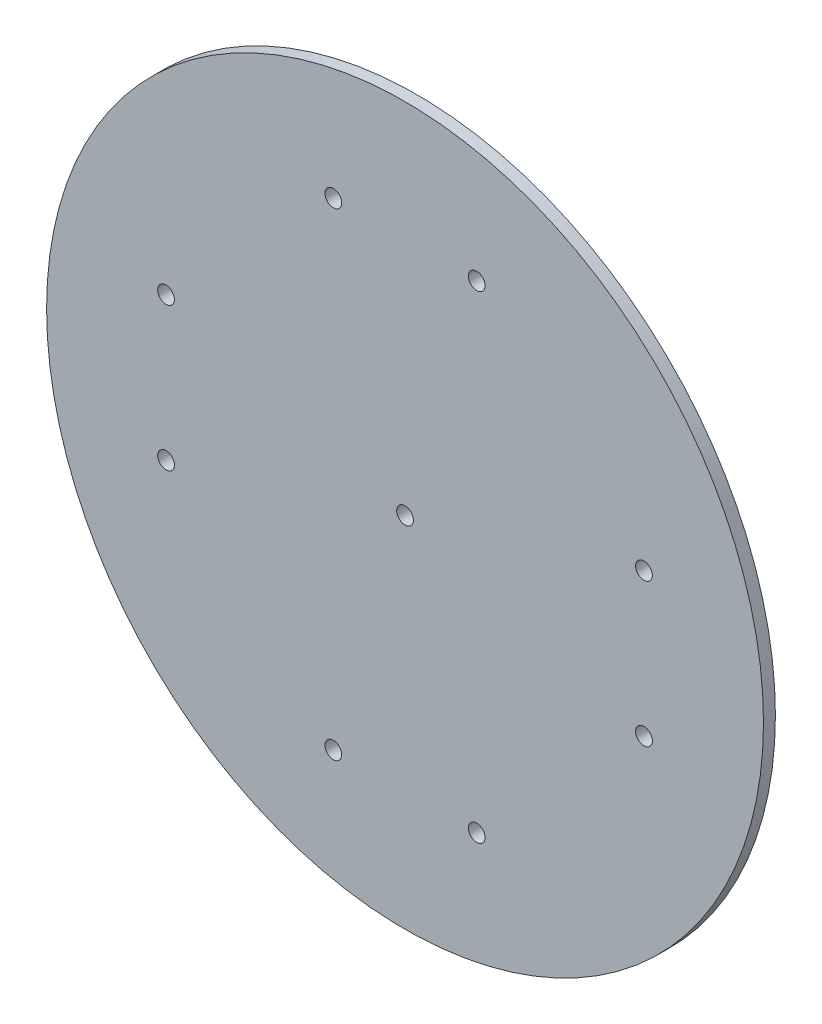
SolidWorks part; units mm, degrees
ref_plane "Front Plane" through (0, 0, 0) normal (0, 0, 1) x (1, 0, 0)
ref_plane "Top Plane" through (0, 0, 0) normal (0, 1, 0) x (1, 0, 0)
ref_plane "Right Plane" through (0, 0, 0) normal (1, 0, 0) x (0, 0, -1)
sketch "Sketch1" plane through (0, 0, 0) normal (0, 0, 1) x (1, 0, 0)
  circle A0 centre (0, 0) radius 75
  dimension "D1" = 150
extrude "Boss-Extrude1" add sketch "Sketch1" along normal blind 2.5
sketch "Sketch2" plane through (0, 0, 0) normal (0, 0, -1) x (-1, 0, 0)
  line L1 (-50, 15) -> (50, 15) construction
  line L2 (-50, 15) -> (-50, -15) construction
  line L3 (-50, -15) -> (50, -15) construction
  line L4 (50, 15) -> (50, -15) construction
  line L5 (-50, 15) -> (50, -15) construction
  line L6 (-50, -15) -> (50, 15) construction
  line L7 (-15, 50) -> (15, 50) construction
  line L8 (-15, 50) -> (-15, -50) construction
  line L9 (-15, -50) -> (15, -50) construction
  line L10 (15, 50) -> (15, -50) construction
  line L11 (-15, 50) -> (15, -50) construction
  line L12 (-15, -50) -> (15, 50) construction
  circle A0 centre (-50, 15) radius 1.75
  circle A1 centre (-50, -15) radius 1.75
  circle A2 centre (-15, -50) radius 1.75
  circle A3 centre (15, -50) radius 1.75
  circle A4 centre (50, -15) radius 1.75
  circle A5 centre (50, 15) radius 1.75
  circle A6 centre (-15, 50) radius 1.75
  circle A7 centre (15, 50) radius 1.75
  point P0 (0, 0)
  point P6 (0, 0)
  dimension "D3" = 3.5
  dimension "D1" = 100
  dimension "D2" = 30
extrude "Cut-Extrude1" cut sketch "Sketch2" against normal through all
sketch "Sketch3" plane through (0, 0, 0) normal (0, 0, -1) x (-1, 0, 0)
  circle A0 centre (0, 0) radius 1.75
  dimension "D1" = 3.5
extrude "Cut-Extrude2" cut sketch "Sketch3" against normal through all
